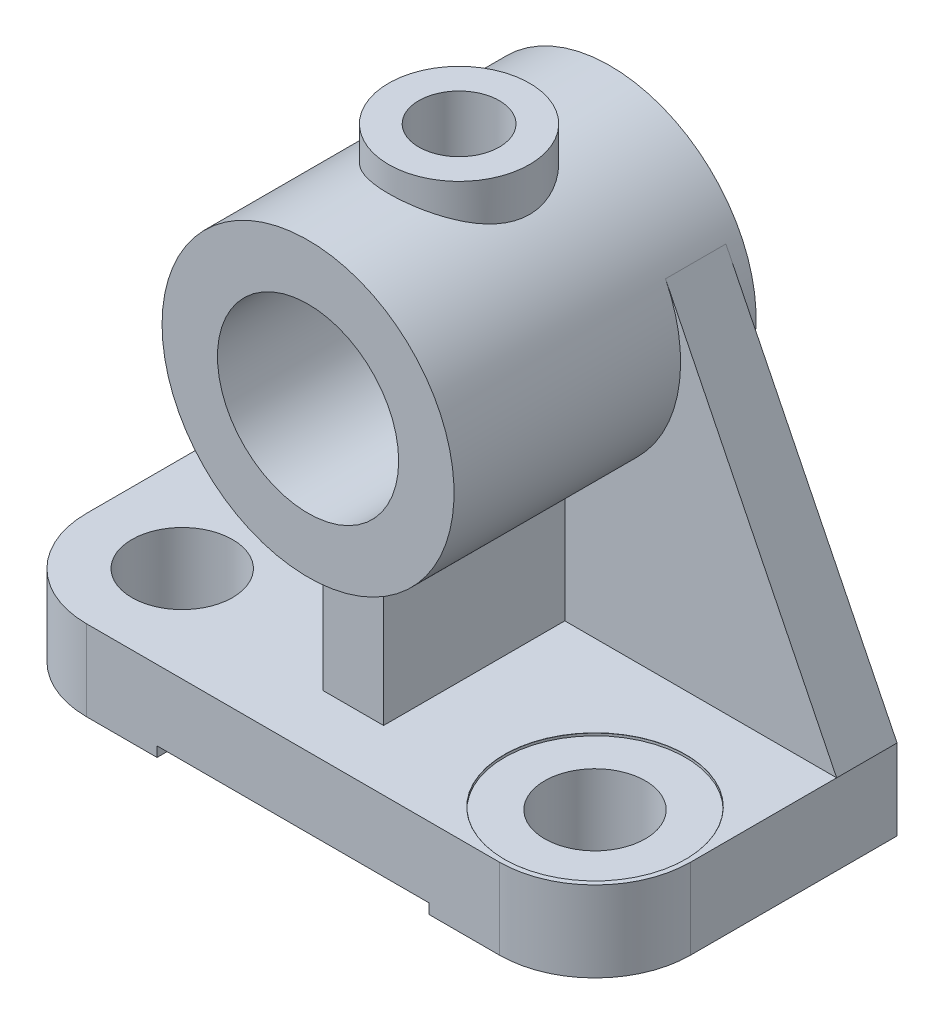
SolidWorks part; units mm, degrees
ref_plane "前视基准面" through (0, 0, 0) normal (0, 0, 1) x (1, 0, 0)
ref_plane "上视基准面" through (0, 0, 0) normal (0, 1, 0) x (1, 0, 0)
ref_plane "右视基准面" through (0, 0, 0) normal (1, 0, 0) x (0, 0, -1)
other "Configuration Table"
sketch "草图3" plane through (0, 0, 0) normal (0, 1, 0) x (1, 0, 0)
  line L1 (0, 0) -> (120, 0)
  line L2 (0, 0) -> (0, -60)
  line L3 (0, -60) -> (120, -60)
  line L4 (120, 0) -> (120, -60)
  dimension "D1" = 120
  dimension "D2" = 60
extrude "凸台-拉伸2" add sketch "草图3" along normal blind 16
fillet "圆角3" radius 19 2 edges at (120, 8, 60) (0, 8, 60)
ref_plane "基准面1" through (0, 0, -3) normal (0, 0, -1) x (-1, 0, 0)
sketch "草图4" plane through (0, 0, -3) normal (0, 0, -1) x (-1, 0, 0)
  line L0 (-60, 0) -> (-60, 69.6368) construction
  line L1 (-19, 0) -> (-101, 0) construction
  line L2 (-120, 0) -> (0, 0) construction
  circle A0 centre (-60, 72) radius 29
  point P6 (0, 0)
  dimension "D1" = 58
  dimension "D2" = 72
extrude "凸台-拉伸3" add sketch "草图4" against normal blind 60 separate body contours A0
sketch "草图5" plane through (0, 0, 57) normal (0, 0, 1) x (1, 0, 0)
  circle A0 centre (60, 72) radius 18
  dimension "D1" = 36
extrude "切除-拉伸1" cut sketch "草图5" against normal through all both
sketch "草图8" plane through (0, 16, 0) normal (0, 1, 0) x (1, 0, 0)
  line L0 (60, -60) -> (60, 19.1362) construction
  line L1 (19, -60) -> (101, -60) construction
  line L2 (46.6627, 3) -> (-46.6627, 3) construction
  circle A0 centre (60, -27) radius 14
  point P6 (0, 0)
  dimension "D1" = 28
  dimension "D2" = 30
ref_plane "基准面2" through (0, 106, 0) normal (0, 1, 0) x (1, 0, 0)
sketch "草图9" plane through (0, 106, 0) normal (0, 1, 0) x (1, 0, 0)
  circle A0 centre (60, -27) radius 14
  dimension "D1" = 28
extrude "凸台-拉伸4" add sketch "草图9" against normal up to surface (16 mm away)
sketch "草图10" plane through (0, 106, 0) normal (0, 1, 0) x (1, 0, 0)
  circle A0 centre (60, -27) radius 8
  point P3 (0, 0)
  dimension "D1" = 16
extrude "切除-拉伸2" cut sketch "草图10" against normal up to surface (16 mm away)
sketch "草图11" plane through (0, 0, 0) normal (0, 0, 1) x (1, 0, 0)
  line L0 (0, 16) -> (33.9981, 84.8413)
  line L3 (120, 16) -> (86.0019, 84.8413)
  line L7 (0, 0) -> (120, 0)
  line L8 (0, 16) -> (0, 0)
  line L9 (120, 16) -> (0, 16)
  line L10 (120, 0) -> (120, 16)
  line L11 (0, 0) -> (120, 0)
  line L12 (0, 16) -> (0, 0)
  line L13 (120, 16) -> (0, 16)
  line L14 (120, 0) -> (120, 16)
  circle A2 centre (60, 72) radius 29
  arc A3 (33.9981, 84.8413) -> (86.0019, 84.8413) centre (60, 72) ccw
  dimension "D1" = 0
  dimension "D2" = 0
extrude "凸台-拉伸8" add sketch "草图11" along normal blind 12 contours A3 L0 L13 L3
ref_plane "基准面3" through (60, 0, 0) normal (1, 0, 0) x (0, 0, -1)
sketch "草图14" plane through (60, 0, 0) normal (1, 0, 0) x (0, 0, -1)
  line L0 (-48, 16) -> (-48, 43)
  line L1 (-13, 16) -> (-41, 16) construction
  line L2 (-57, 43) -> (-12, 43) construction
  line L3 (-12, 16) -> (-12, 84.8413) construction
  dimension "D1" = 36
rib "筋26" sketch "草图14" sketch "草图14" thickness 12 extrusion direction parallel to sketch draft on no parameters "D1"=12
sketch "草图16" plane through (0, 0, 60) normal (0, 0, 1) x (1, 0, 0)
  line L0 (33, 0) -> (33, 2)
  line L1 (19, 0) -> (101, 0) construction
  line L2 (33, 2) -> (87, 2)
  line L3 (87, 2) -> (87, 0)
  line L4 (87, 0) -> (60, 0)
  line L5 (60, 0) -> (33, 0)
  dimension "D1" = 2
  dimension "D2" = 27
  dimension "D3" = 27
extrude "切除-拉伸3" cut sketch "草图16" against normal through all
ref_plane "基准面4" through (101, 16, 60) normal (1, 0, 0) x (0, 0, -1)
sketch "草图19" plane through (0, 16, 0) normal (0, 1, 0) x (1, 0, 0)
  line L4 (87, -60) -> (101, -60)
  line L5 (87, 0) -> (87, -60)
  line L6 (120, 0) -> (87, 0)
  line L7 (120, -41) -> (120, 0)
  line L8 (87, -60) -> (101, -60)
  line L9 (87, 0) -> (87, -60)
  line L10 (120, 0) -> (87, 0)
  line L11 (120, -41) -> (120, 0)
  arc A1 (101, -60) -> (120, -41) centre (101, -41) ccw
  arc A2 (101, -60) -> (120, -41) centre (101, -41) ccw
  point P4 (0, 0)
  dimension "D1" = 0
hole_wizard "M18 六角头螺栓C级的柱形沉头孔1" positions "3D草图3" profile "草图20" counterbore size "M18" standard "GB" end condition through all
sketch3d "3D草图3"
  point P0 (101, 16, 41)
sketch "草图20" plane through (101, 16, 41) normal (1, 0, 0) x (0, 0, 1)
  line L0 (0, 0) -> (0, 16)
  line L1 (0, 16) -> (10, 16)
  line L3 (10, 16) -> (10, 0.5)
  line L4 (18, 0.5) -> (10, 0.5)
  line L5 (18, 0.5) -> (18, 0.021)
  line L6 (18, 0.021) -> (18.025, 0)
  line L7 (18.025, 0) -> (0, 0)
  line L8 (-18, 0.021) -> (-18.025, 0) construction
  line L11 (0, -6.35) -> (0, 107.95) construction
  dimension "通孔孔直径" = 20
  dimension "通孔孔深度" = 16
  dimension "柱形沉头孔直径" = 36
  dimension "柱形沉头孔深度" = 0.5
  dimension "近端锥形沉头孔直径" = 36.05
  dimension "近端锥形沉头孔角度" = 100
sketch "草图21" plane through (0, 0, 0) normal (0, -1, 0) x (1, 0, 0)
  line L4 (0, 0) -> (33, 0)
  line L5 (33, 0) -> (33, 60)
  line L6 (33, 60) -> (19, 60)
  line L7 (0, 41) -> (0, 0)
  line L8 (0, 0) -> (33, 0)
  line L9 (33, 0) -> (33, 60)
  line L10 (33, 60) -> (19, 60)
  line L11 (0, 41) -> (0, 0)
  arc A1 (19, 60) -> (0, 41) centre (19, 41) ccw
  arc A2 (19, 60) -> (0, 41) centre (19, 41) ccw
  dimension "D1" = 0
hole_wizard "M18 六角头螺栓C级的柱形沉头孔2" positions "3D草图4" profile "草图22" counterbore size "M18" standard "GB" end condition through all
sketch3d "3D草图4"
  point P3 (19, 0, 41)
sketch "草图22" plane through (19, 0, 41) normal (1, 0, 0) x (0, 0, -1)
  line L0 (0, 0) -> (0, 106)
  line L1 (0, 106) -> (10, 106)
  line L3 (10, 106) -> (10, 0.5)
  line L4 (18, 0.5) -> (10, 0.5)
  line L5 (18, 0.5) -> (18, 0.021)
  line L6 (18, 0.021) -> (18.025, 0)
  line L7 (18.025, 0) -> (0, 0)
  line L8 (-18, 0.021) -> (-18.025, 0) construction
  line L11 (0, -6.35) -> (0, 107.95) construction
  dimension "通孔孔直径" = 20
  dimension "通孔孔深度" = 106
  dimension "柱形沉头孔直径" = 36
  dimension "柱形沉头孔深度" = 0.5
  dimension "近端锥形沉头孔直径" = 36.05
  dimension "近端锥形沉头孔角度" = 100
